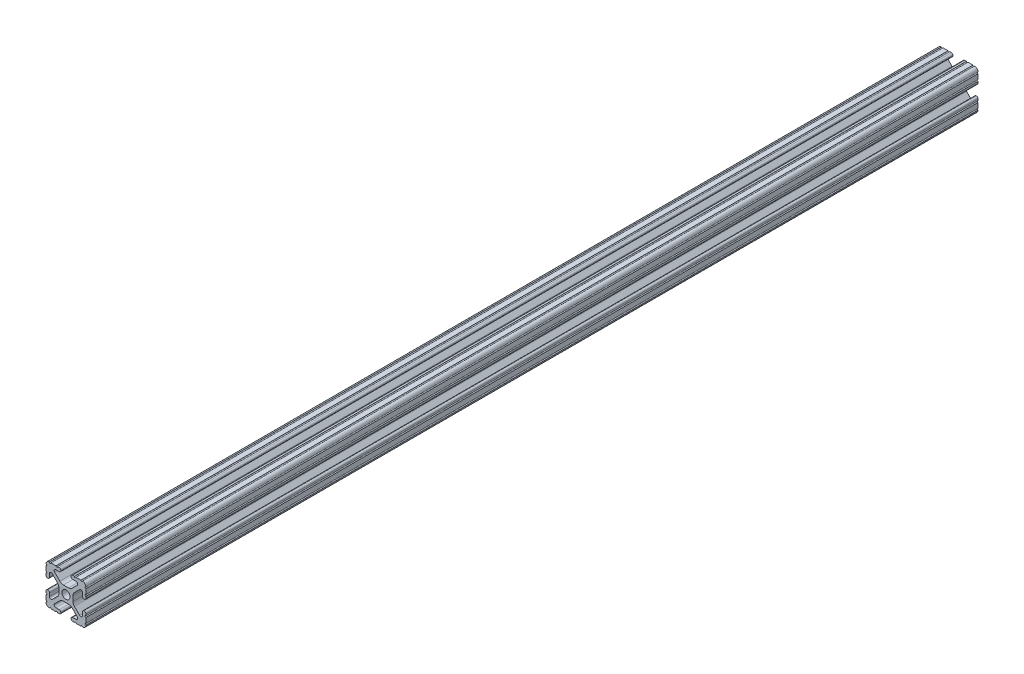
SolidWorks part; units mm, degrees
material "6061 Alloy"
ref_plane "Front Plane" through (0, 0, 0) normal (0, 0, 1) x (1, 0, 0)
ref_plane "Top Plane" through (0, 0, 0) normal (0, 1, 0) x (1, 0, 0)
ref_plane "Right Plane" through (0, 0, 0) normal (1, 0, 0) x (0, 0, -1)
sketch "Sketch1" plane through (0, 0, 0) normal (0, 0, 1) x (1, 0, 0)
  line L88 (-7.1797, -8.6452) -> (-3.9523, -5.4237)
  line L89 (-1.7093, -4.4958) -> (1.7093, -4.4958)
  line L90 (3.9523, -5.4237) -> (7.1797, -8.6452)
  line L91 (6.4164, -10.4902) -> (4.2875, -10.4902)
  line L92 (3.2385, -11.5392) -> (3.2385, -11.651)
  line L93 (4.2875, -12.7) -> (5.3171, -12.7)
  line L94 (6.3331, -12.7) -> (9.5504, -12.7)
  line L95 (12.7, -9.5504) -> (12.7, -6.3331)
  line L96 (12.7, -5.3171) -> (12.7, -4.2875)
  line L97 (11.651, -3.2385) -> (11.5392, -3.2385)
  line L98 (10.4902, -4.2875) -> (10.4902, -6.4021)
  line L99 (8.7371, -7.1294) -> (5.441, -3.8408)
  line L100 (4.5085, -1.5932) -> (4.5085, 1.5932)
  line L101 (5.441, 3.8408) -> (8.7371, 7.1294)
  line L102 (10.4902, 6.4021) -> (10.4902, 4.2875)
  line L103 (11.5392, 3.2385) -> (11.651, 3.2385)
  line L104 (12.7, 4.2875) -> (12.7, 5.3171)
  line L105 (12.7, 6.3331) -> (12.7, 9.5504)
  line L106 (9.5504, 12.7) -> (6.3331, 12.7)
  line L107 (5.3171, 12.7) -> (4.2875, 12.7)
  line L108 (3.2385, 11.651) -> (3.2385, 11.5392)
  line L109 (4.2875, 10.4902) -> (6.4768, 10.4902)
  line L110 (7.207, 8.7244) -> (3.8983, 5.4232)
  line L111 (1.6558, 4.4958) -> (-1.6558, 4.4958)
  line L112 (-3.8983, 5.4232) -> (-7.207, 8.7244)
  line L113 (-6.4768, 10.4902) -> (-4.2875, 10.4902)
  line L114 (-3.2385, 11.5392) -> (-3.2385, 11.651)
  line L115 (-4.2875, 12.7) -> (-5.3171, 12.7)
  line L116 (-6.3331, 12.7) -> (-9.5504, 12.7)
  line L117 (-12.7, 9.5504) -> (-12.7, 6.3331)
  line L118 (-12.7, 5.3171) -> (-12.7, 4.2875)
  line L119 (-11.651, 3.2385) -> (-11.5392, 3.2385)
  line L120 (-10.4902, 4.2875) -> (-10.4902, 6.4021)
  line L121 (-8.7371, 7.1294) -> (-5.441, 3.8408)
  line L122 (-4.5085, 1.5932) -> (-4.5085, -1.5932)
  line L123 (-5.441, -3.8408) -> (-8.7371, -7.1294)
  line L124 (-10.4902, -6.4021) -> (-10.4902, -4.2875)
  line L125 (-11.5392, -3.2385) -> (-11.651, -3.2385)
  line L126 (-12.7, -4.2875) -> (-12.7, -5.3171)
  line L127 (-12.7, -6.3331) -> (-12.7, -9.5504)
  line L128 (-9.5504, -12.7) -> (-6.3331, -12.7)
  line L129 (-5.3171, -12.7) -> (-4.2875, -12.7)
  line L130 (-3.2385, -11.651) -> (-3.2385, -11.5392)
  line L131 (-4.2875, -10.4902) -> (-6.4164, -10.4902)
  circle A1 centre (0, 0) radius 2.6035
  arc A104 (-7.1797, -8.6452) -> (-6.4164, -10.4902) centre (-6.4164, -9.4098) ccw
  arc A105 (-1.7093, -4.4958) -> (-3.9523, -5.4237) centre (-1.7093, -7.6708) ccw
  arc A106 (3.9523, -5.4237) -> (1.7093, -4.4958) centre (1.7093, -7.6708) ccw
  arc A107 (6.4164, -10.4902) -> (7.1797, -8.6452) centre (6.4164, -9.4098) ccw
  arc A108 (4.2875, -10.4902) -> (3.2385, -11.5392) centre (4.2875, -11.5392) ccw
  arc A109 (3.2385, -11.651) -> (4.2875, -12.7) centre (4.2875, -11.651) ccw
  arc A110 (6.3331, -12.7) -> (5.3171, -12.7) centre (5.8251, -12.7) ccw
  arc A111 (10.5664, -12.6998) -> (9.5504, -12.7) centre (10.0584, -12.7) ccw
  arc A112 (10.5664, -12.6998) -> (12.6998, -10.5664) centre (10.5918, -10.5918) ccw
  arc A113 (12.7, -9.5504) -> (12.6998, -10.5664) centre (12.7, -10.0584) ccw
  arc A114 (12.7, -5.3171) -> (12.7, -6.3331) centre (12.7, -5.8251) ccw
  arc A115 (12.7, -4.2875) -> (11.651, -3.2385) centre (11.651, -4.2875) ccw
  arc A116 (11.5392, -3.2385) -> (10.4902, -4.2875) centre (11.5392, -4.2875) ccw
  arc A117 (8.7371, -7.1294) -> (10.4902, -6.4021) centre (9.4628, -6.4021) ccw
  arc A118 (4.5085, -1.5932) -> (5.441, -3.8408) centre (7.6835, -1.5932) ccw
  arc A119 (5.441, 3.8408) -> (4.5085, 1.5932) centre (7.6835, 1.5932) ccw
  arc A120 (10.4902, 6.4021) -> (8.7371, 7.1294) centre (9.4628, 6.4021) ccw
  arc A121 (10.4902, 4.2875) -> (11.5392, 3.2385) centre (11.5392, 4.2875) ccw
  arc A122 (11.651, 3.2385) -> (12.7, 4.2875) centre (11.651, 4.2875) ccw
  arc A123 (12.7, 6.3331) -> (12.7, 5.3171) centre (12.7, 5.8251) ccw
  arc A124 (12.6998, 10.5664) -> (12.7, 9.5504) centre (12.7, 10.0584) ccw
  arc A125 (12.6998, 10.5664) -> (10.5664, 12.6998) centre (10.5918, 10.5918) ccw
  arc A126 (9.5504, 12.7) -> (10.5664, 12.6998) centre (10.0584, 12.7) ccw
  arc A127 (5.3171, 12.7) -> (6.3331, 12.7) centre (5.8251, 12.7) ccw
  arc A128 (4.2875, 12.7) -> (3.2385, 11.651) centre (4.2875, 11.651) ccw
  arc A129 (3.2385, 11.5392) -> (4.2875, 10.4902) centre (4.2875, 11.5392) ccw
  arc A130 (7.207, 8.7244) -> (6.4768, 10.4902) centre (6.4768, 9.4563) ccw
  arc A131 (1.6558, 4.4958) -> (3.8983, 5.4232) centre (1.6558, 7.6708) ccw
  arc A132 (-3.8983, 5.4232) -> (-1.6558, 4.4958) centre (-1.6558, 7.6708) ccw
  arc A133 (-6.4768, 10.4902) -> (-7.207, 8.7244) centre (-6.4768, 9.4563) ccw
  arc A134 (-4.2875, 10.4902) -> (-3.2385, 11.5392) centre (-4.2875, 11.5392) ccw
  arc A135 (-3.2385, 11.651) -> (-4.2875, 12.7) centre (-4.2875, 11.651) ccw
  arc A136 (-6.3331, 12.7) -> (-5.3171, 12.7) centre (-5.8251, 12.7) ccw
  arc A137 (-10.5664, 12.6998) -> (-9.5504, 12.7) centre (-10.0584, 12.7) ccw
  arc A138 (-10.5664, 12.6998) -> (-12.6998, 10.5664) centre (-10.5918, 10.5918) ccw
  arc A139 (-12.7, 9.5504) -> (-12.6998, 10.5664) centre (-12.7, 10.0584) ccw
  arc A140 (-12.7, 5.3171) -> (-12.7, 6.3331) centre (-12.7, 5.8251) ccw
  arc A141 (-12.7, 4.2875) -> (-11.651, 3.2385) centre (-11.651, 4.2875) ccw
  arc A142 (-11.5392, 3.2385) -> (-10.4902, 4.2875) centre (-11.5392, 4.2875) ccw
  arc A143 (-8.7371, 7.1294) -> (-10.4902, 6.4021) centre (-9.4628, 6.4021) ccw
  arc A144 (-4.5085, 1.5932) -> (-5.441, 3.8408) centre (-7.6835, 1.5932) ccw
  arc A145 (-5.441, -3.8408) -> (-4.5085, -1.5932) centre (-7.6835, -1.5932) ccw
  arc A146 (-10.4902, -6.4021) -> (-8.7371, -7.1294) centre (-9.4628, -6.4021) ccw
  arc A147 (-10.4902, -4.2875) -> (-11.5392, -3.2385) centre (-11.5392, -4.2875) ccw
  arc A148 (-11.651, -3.2385) -> (-12.7, -4.2875) centre (-11.651, -4.2875) ccw
  arc A149 (-12.7, -6.3331) -> (-12.7, -5.3171) centre (-12.7, -5.8251) ccw
  arc A150 (-12.6998, -10.5664) -> (-12.7, -9.5504) centre (-12.7, -10.0584) ccw
  arc A151 (-12.6998, -10.5664) -> (-10.5664, -12.6998) centre (-10.5918, -10.5918) ccw
  arc A152 (-9.5504, -12.7) -> (-10.5664, -12.6998) centre (-10.0584, -12.7) ccw
  arc A153 (-5.3171, -12.7) -> (-6.3331, -12.7) centre (-5.8251, -12.7) ccw
  arc A154 (-4.2875, -12.7) -> (-3.2385, -11.651) centre (-4.2875, -11.651) ccw
  arc A155 (-3.2385, -11.5392) -> (-4.2875, -10.4902) centre (-4.2875, -11.5392) ccw
extrude "Boss-Extrude1" add sketch "Sketch1" along normal mid plane 568.325
